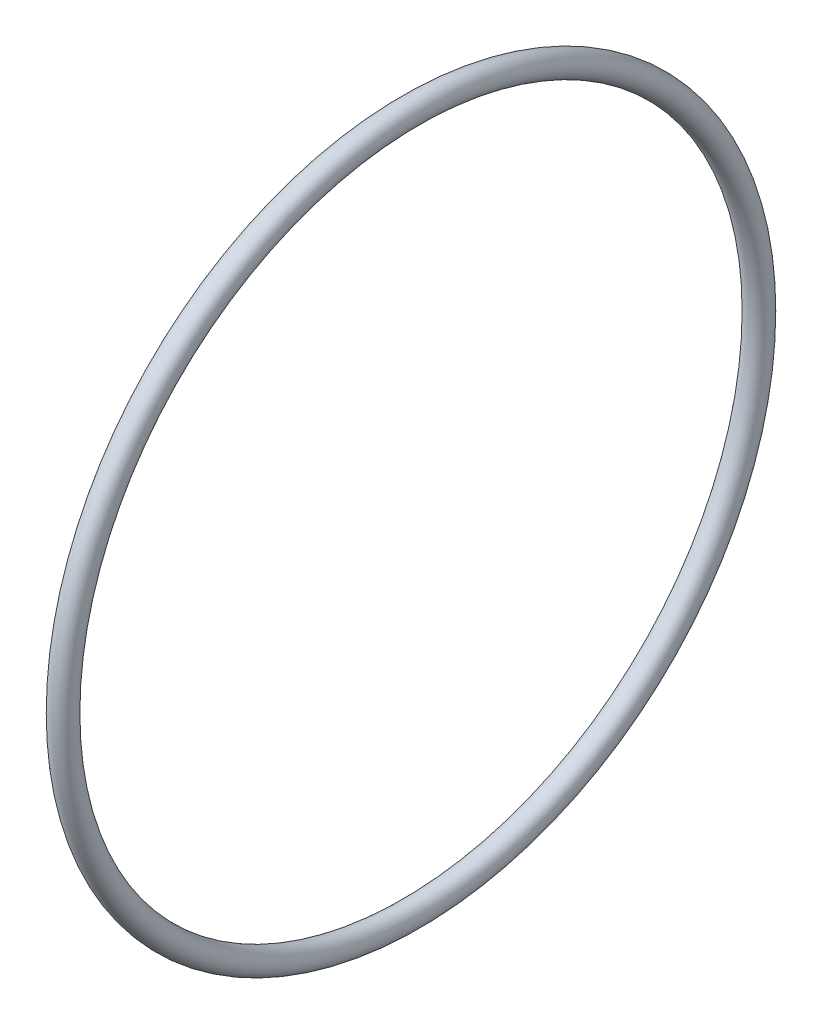
SolidWorks part; units mm, degrees
material "天然橡胶"
ref_plane "前视基准面" through (0, 0, 0) normal (0, 0, 1) x (1, 0, 0)
ref_plane "上视基准面" through (0, 0, 0) normal (0, 1, 0) x (1, 0, 0)
ref_plane "右视基准面" through (0, 0, 0) normal (1, 0, 0) x (0, 0, -1)
ref_plane "基准面1" through (0, 0, 0) normal (1, 0, 0) x (0, 0, -1)
sketch "草图1" plane through (0, 0, 0) normal (0, 0, 1) x (1, 0, 0)
  line L0 (0, 0) -> (9.2995, 0) construction
  circle A0 centre (0, 19) radius 0.65
  circle A1 centre (0, -19) radius 0.65 construction
  dimension "D1" = 36.7
  dimension "D2" = 1.3
revolve "旋转1" add sketch "草图1" angle 360 about L0
